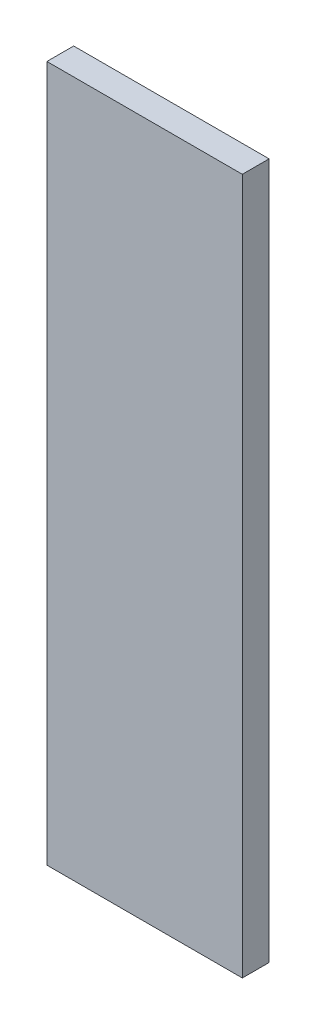
SolidWorks part; units mm, degrees
ref_plane "Front Plane" through (0, 0, 0) normal (0, 0, 1) x (1, 0, 0)
ref_plane "Top Plane" through (0, 0, 0) normal (0, 1, 0) x (1, 0, 0)
ref_plane "Right Plane" through (0, 0, 0) normal (1, 0, 0) x (0, 0, -1)
sketch "Sketch1" plane through (0, 0, 0) normal (0, 0, 1) x (1, 0, 0)
  line L1 (0, 0) -> (18.542, 0)
  line L2 (0, 0) -> (0, 66.04)
  line L3 (0, 66.04) -> (18.542, 66.04)
  line L4 (18.542, 0) -> (18.542, 66.04)
  dimension "D1" = 66.04
  dimension "D2" = 18.542
extrude "Boss-Extrude1" add sketch "Sketch1" along normal blind 2.54
